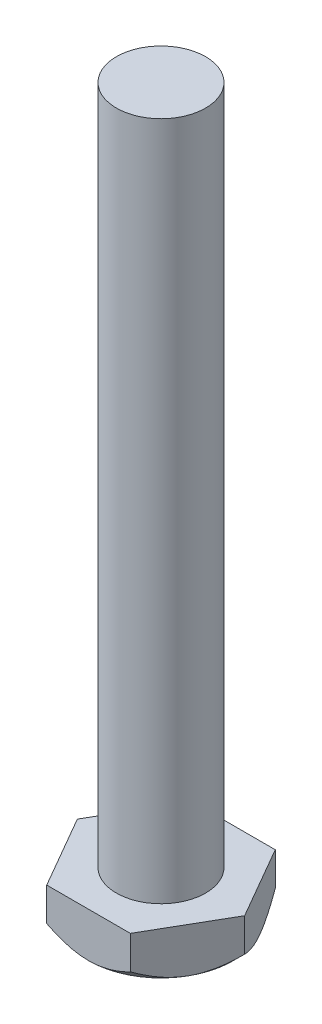
SolidWorks part; units mm, degrees
ref_plane "Front Plane" through (0, 0, 0) normal (0, 0, 1) x (1, 0, 0)
ref_plane "Top Plane" through (0, 0, 0) normal (0, 1, 0) x (1, 0, 0)
ref_plane "Right Plane" through (0, 0, 0) normal (1, 0, 0) x (0, 0, -1)
sketch "Sketch1" plane through (0, 0, 0) normal (0, 1, 0) x (1, 0, 0)
  line L1 (7.5056, 0) -> (3.7528, 6.5)
  line L2 (3.7528, 6.5) -> (-3.7528, 6.5)
  line L3 (-3.7528, 6.5) -> (-7.5056, 0)
  line L4 (-7.5056, 0) -> (-3.7528, -6.5)
  line L5 (-3.7528, -6.5) -> (3.7528, -6.5)
  line L6 (3.7528, -6.5) -> (7.5056, 0)
  circle A0 centre (0, 0) radius 6.5 construction
  dimension "D1" = 13
extrude "Boss-Extrude1" add sketch "Sketch1" along normal blind 4
sketch "Sketch2" plane through (0, 0, 0) normal (0, -1, 0) x (-1, 0, 0)
  circle A0 centre (0, 0) radius 6.5
extrude "Cut-Extrude2" cut sketch "Sketch2" against normal through all draft 45 flip side to cut
sketch "Sketch3" plane through (0, 4, 0) normal (0, 1, 0) x (1, 0, 0)
  circle A0 centre (0, 0) radius 4
  dimension "D1" = 8
extrude "Boss-Extrude2" add sketch "Sketch3" along normal blind 61
